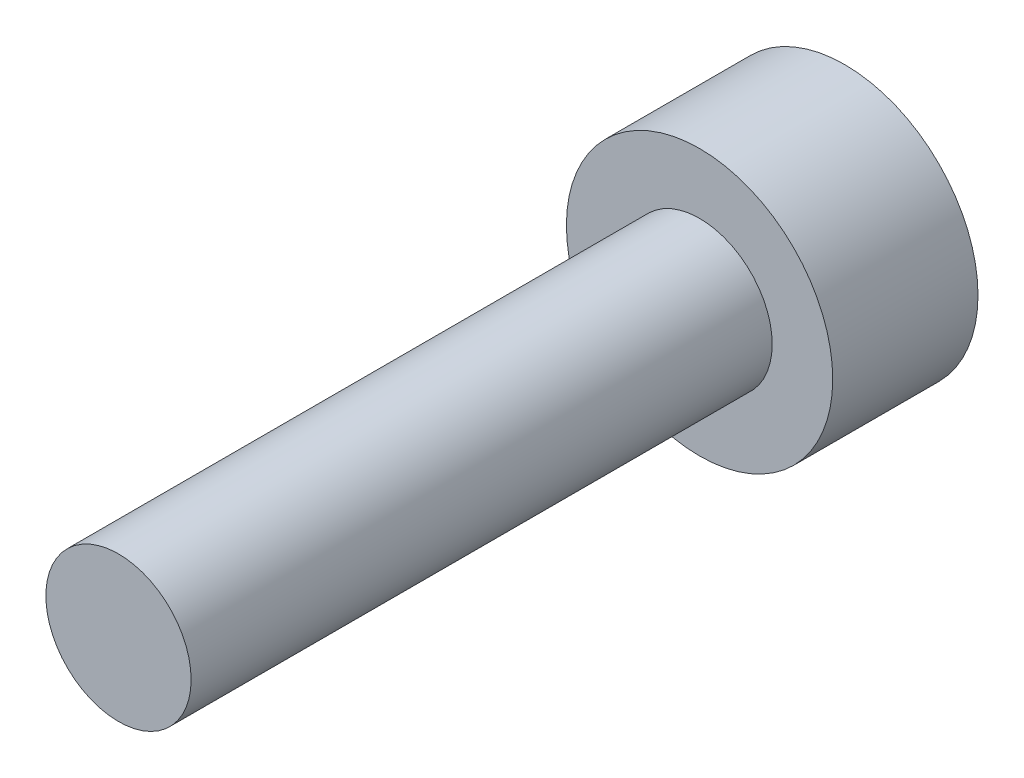
SolidWorks part; units mm, degrees
ref_plane "正面" through (0, 0, 0) normal (0, 0, 1) x (1, 0, 0)
ref_plane "平面" through (0, 0, 0) normal (0, 1, 0) x (1, 0, 0)
ref_plane "右側面" through (0, 0, 0) normal (1, 0, 0) x (0, 0, -1)
sketch "ｽｹｯﾁ1" plane through (0, 0, 0) normal (0, 0, 1) x (1, 0, 0)
  circle A0 centre (0, 0) radius 2.75
  dimension "D1" = 5.5
extrude "ﾎﾞｽ - 押し出し1" add sketch "ｽｹｯﾁ1" along normal blind 3
sketch "ｽｹｯﾁ2" plane through (0, 0, 3) normal (0, 0, 1) x (1, 0, 0)
  circle A0 centre (0, 0) radius 1.5
  dimension "D1" = 3
extrude "ﾎﾞｽ - 押し出し2" add sketch "ｽｹｯﾁ2" along normal blind 12
cosmetic thread "ねじ山1" parameters "D2"=3
sketch "ｽｹｯﾁ3" plane through (0, 0, 0) normal (0, 0, -1) x (-1, 0, 0)
  line L1 (1.6636, -0.3991) -> (1.1774, 1.2412)
  line L2 (1.1774, 1.2412) -> (-0.4862, 1.6403)
  line L3 (-0.4862, 1.6403) -> (-1.6636, 0.3991)
  line L4 (-1.6636, 0.3991) -> (-1.1774, -1.2412)
  line L5 (-1.1774, -1.2412) -> (0.4862, -1.6403)
  line L6 (0.4862, -1.6403) -> (1.6636, -0.3991)
  circle A0 centre (0, 0) radius 1.4816 construction
extrude "ｶｯﾄ - 押し出し1" cut sketch "ｽｹｯﾁ3" against normal blind 2
